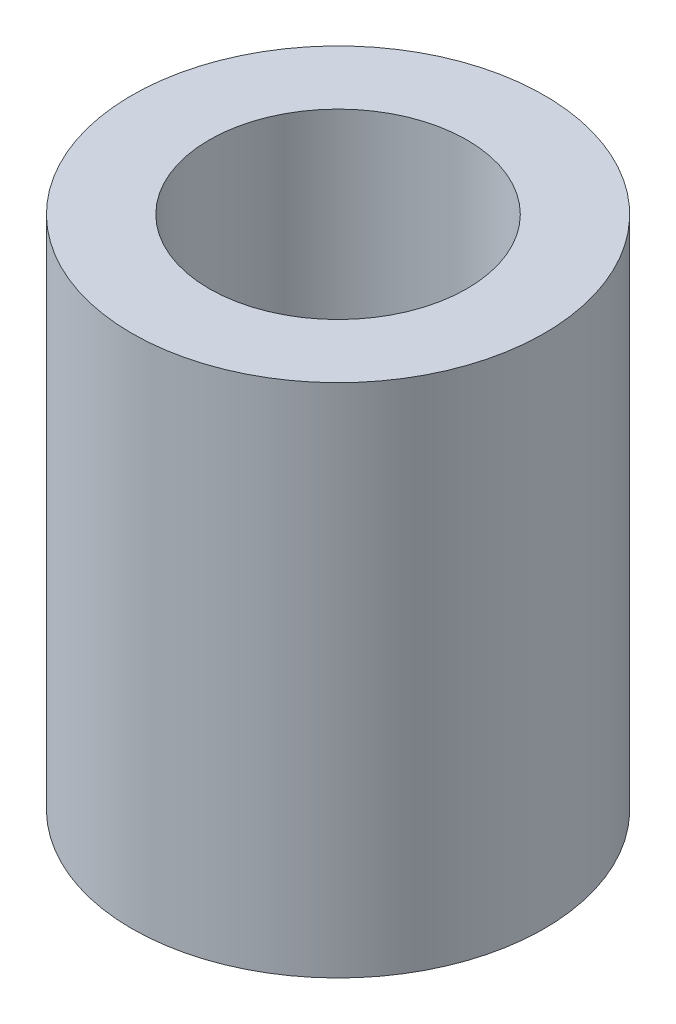
SolidWorks part; units mm, degrees
material "ABS"
ref_plane "前视基准面" through (0, 0, 0) normal (0, 0, 1) x (1, 0, 0)
ref_plane "上视基准面" through (0, 0, 0) normal (0, 1, 0) x (1, 0, 0)
ref_plane "右视基准面" through (0, 0, 0) normal (1, 0, 0) x (0, 0, -1)
sketch "草图1" plane through (0, 0, 0) normal (0, 1, 0) x (1, 0, 0)
  circle A0 centre (0, 0) radius 1.25
  circle A1 centre (0, 0) radius 2
  dimension "D1" = 2.5
  dimension "D2" = 4
extrude "凸台-拉伸1" add sketch "草图1" along normal blind 5
